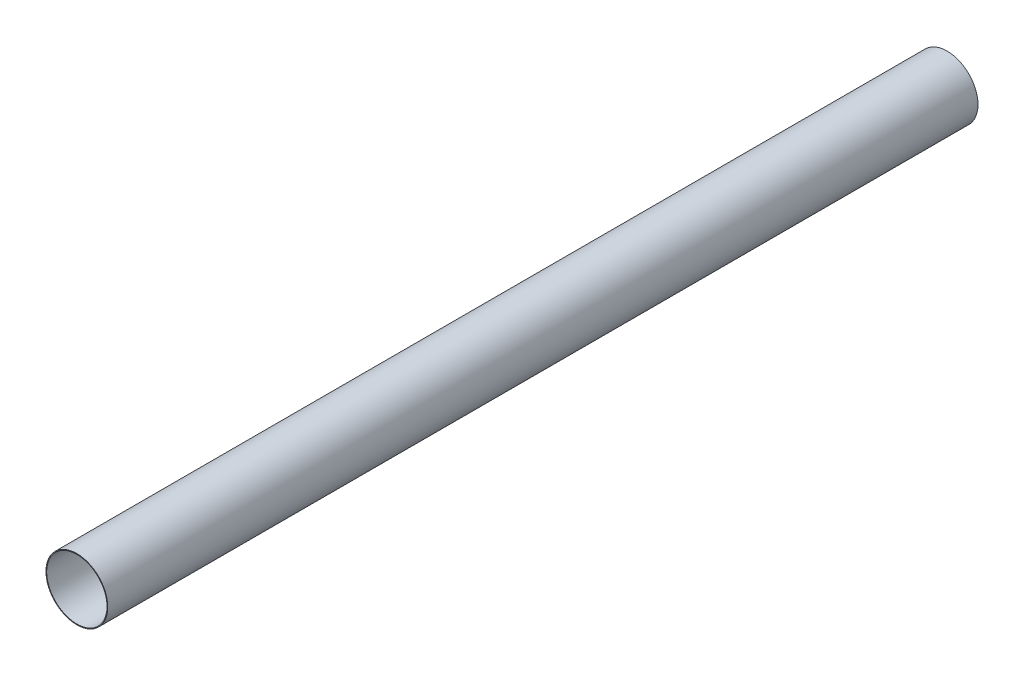
SolidWorks part; units mm, degrees
ref_plane "Front Plane" through (0, 0, 0) normal (0, 0, 1) x (1, 0, 0)
ref_plane "Top Plane" through (0, 0, 0) normal (0, 1, 0) x (1, 0, 0)
ref_plane "Right Plane" through (0, 0, 0) normal (1, 0, 0) x (0, 0, -1)
sketch "Sketch1" plane through (0, 0, 0) normal (0, 0, 1) x (1, 0, 0)
  circle A0 centre (0, 0) radius 21.3
  circle A1 centre (0, 0) radius 20.8
  dimension "D1" = 42.6
  dimension "D2" = 0.5
extrude "Boss-Extrude1" add sketch "Sketch1" along normal mid plane 600
equation "\"6f\"=10"
